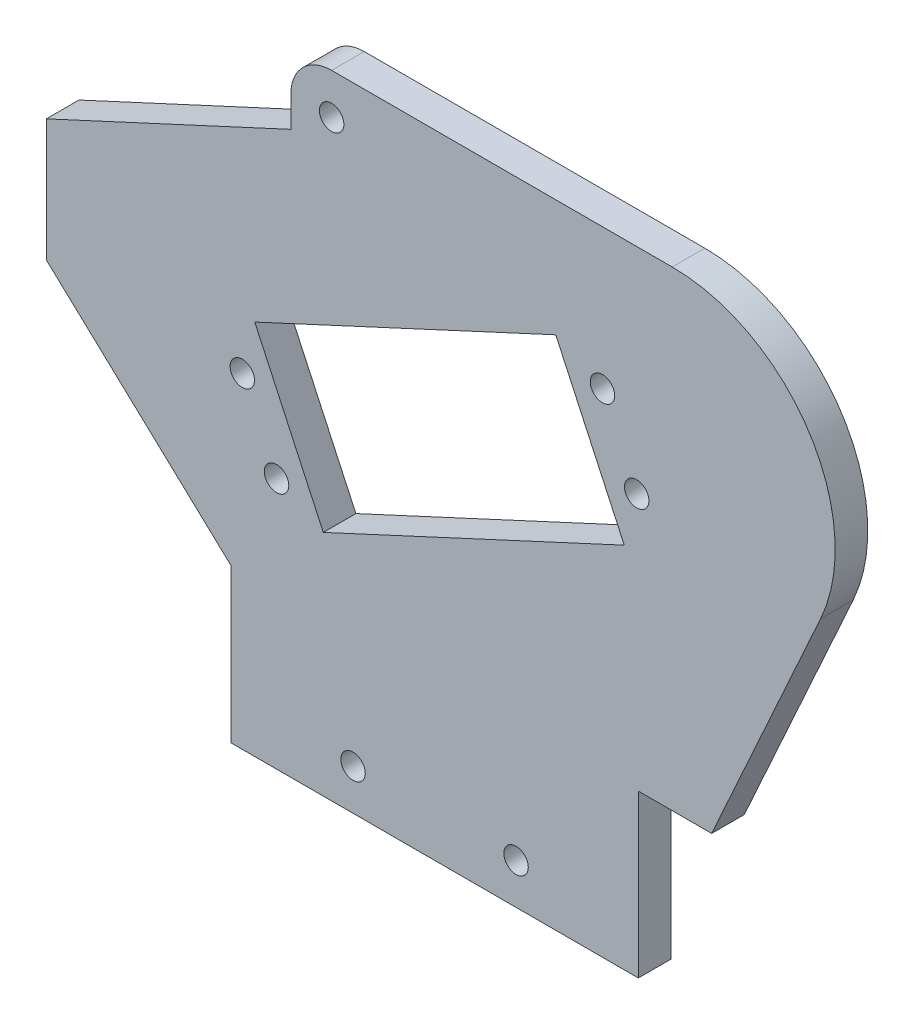
SolidWorks part; units mm, degrees
material "Acrílico (Impacto medio-alto)"
ref_plane "Piano frontale" through (0, 0, 0) normal (0, 0, 1) x (1, 0, 0)
ref_plane "Piano superiore" through (0, 0, 0) normal (0, 1, 0) x (1, 0, 0)
ref_plane "Piano destro" through (0, 0, 0) normal (1, 0, 0) x (0, 0, -1)
sketch "Schizzo1" plane through (0, 0, 0) normal (0, 0, 1) x (1, 0, 0)
  line L0 (15, -50) -> (-35, -50)
  line L1 (0, 0) -> (0, -50)
  line L2 (-35, -50) -> (-35, -31.1401)
  line L3 (-35, -31.1401) -> (-57.6274, -10.022)
  line L4 (-57.6274, -10.022) -> (-57.6274, 4.978)
  line L5 (-57.6274, 4.978) -> (-27.6274, 18.8599)
  line L6 (-27.6274, 18.8599) -> (-27.6274, 22.6274)
  line L7 (-22.6274, 27.6274) -> (19.1556, 27.6274)
  line L8 (0, 0) -> (40.5931, 0) construction
  line L10 (15, -50) -> (37.3726, -0.6274)
  line L11 (-22.6274, 22.6274) -> (0, 0) construction
  circle A0 centre (0, 0) radius 2.5
  arc A1 (19.1556, 27.6274) -> (37.3726, -0.6274) centre (19.1556, 7.6274) cw
  circle A2 centre (-20, -45) radius 1.5
  circle A3 centre (0, -45) radius 1.5
  arc A6 (-27.6274, 22.6274) -> (-22.6274, 27.6274) centre (-22.6274, 22.6274) cw
  circle A7 centre (-22.6274, 22.6274) radius 1.5
  dimension "D1" = 5
  dimension "D5" = 20
  dimension "D6" = 3
  dimension "D7" = 3
  dimension "D11" = 95
  dimension "D12" = 30
  dimension "D14" = 5
  dimension "D15" = 3
  dimension "D2" = 50
  dimension "D3" = 50
  dimension "D4" = 15
  dimension "D8" = 15
  dimension "D9" = 5
  dimension "D10" = 5
  dimension "D13" = 50
  dimension "D16" = 135
  dimension "D17" = 32
  dimension "D18" = 15
extrude "Estrusione-Estrusione1" add sketch "Schizzo1" along normal blind 4
sketch "Schizzo2" plane through (0, 0, 4) normal (0, 0, 1) x (1, 0, 0)
  line L0 (0, 0) -> (-27.8561, -12.9046)
  line L1 (0, 0) -> (9.0736, 4.2034)
  line L3 (-23.6527, -21.9782) -> (13.2771, -4.8702)
  line L4 (-23.6527, -21.9782) -> (-32.0595, -3.8309)
  line L5 (-32.0595, -3.8309) -> (4.8702, 13.2771)
  line L6 (13.2771, -4.8702) -> (4.8702, 13.2771)
  point P9 (-27.8561, -12.9046)
  point P10 (9.0736, 4.2034)
  circle M13 centre (0, 0) radius 2.5
  dimension "D1" = 30.7
  dimension "D2" = 10
  dimension "D3" = 40.7
  dimension "D4" = 20
  dimension "D5" = 270
  dimension "D6" = 270
extrude "Taglio-Estrusione1" cut sketch "Schizzo2" against normal through all contours L1 L6 L5 L4 L0 M13 | L3 L6 L1 L0 L4 M13
sketch "Schizzo3" plane through (0, 0, 4) normal (0, 0, 1) x (1, 0, 0)
  line L0 (9.0736, 4.2034) -> (-27.8561, -12.9046) construction
  line L1 (-29.3838, -19.1228) -> (14.8048, 1.348)
  line L2 (-29.3838, -19.1228) -> (-33.5873, -10.0491)
  line L3 (-33.5873, -10.0491) -> (10.6014, 10.4216)
  line L4 (14.8048, 1.348) -> (10.6014, 10.4216)
  line L5 (-29.3838, -19.1228) -> (10.6014, 10.4216) construction
  line L6 (-33.5873, -10.0491) -> (14.8048, 1.348) construction
  line L7 (13.2771, -4.8702) -> (4.8702, 13.2771) construction
  line L8 (-23.6527, -21.9782) -> (-32.0595, -3.8309) construction
  line L9 (-13.5947, 4.7231) -> (-5.1878, -13.4242) construction
  line L10 (-32.0595, -3.8309) -> (4.8702, 13.2771) construction
  line L11 (-23.6527, -21.9782) -> (13.2771, -4.8702) construction
  circle A0 centre (10.6014, 10.4216) radius 1.5
  circle A1 centre (14.8048, 1.348) radius 1.5
  circle A2 centre (-29.3838, -19.1228) radius 1.5
  circle A3 centre (-33.5873, -10.0491) radius 1.5
  point P0 (-9.3912, -4.3506)
  point P17 (-9.3912, -4.3506)
  dimension "D6" = 3
  dimension "D7" = 3
  dimension "D8" = 3
  dimension "D9" = 3
  dimension "D1" = 4
  dimension "D2" = 10
  dimension "D3" = 270
  dimension "D4" = 270
  dimension "D5" = 270
  dimension "D10" = 4
extrude "Taglio-Estrusione2" cut sketch "Schizzo3" against normal through all contours A3 | A2 | A1 | A0
sketch "Croquis1" plane through (0, 0, 0) normal (0, 0, -1) x (-1, 0, 0)
  line L0 (-15, -50) -> (-37.3726, -0.6274) construction
  line L1 (-15, -50) -> (-24, -50)
  line L2 (-15, -50) -> (-15, -30.1385)
  line L3 (-15, -30.1385) -> (-24, -30.1385)
  line L4 (-24, -50) -> (-24, -30.1385)
  dimension "D1" = 9
extrude "Cortar-Extruir1" cut sketch "Croquis1" against normal blind 10
